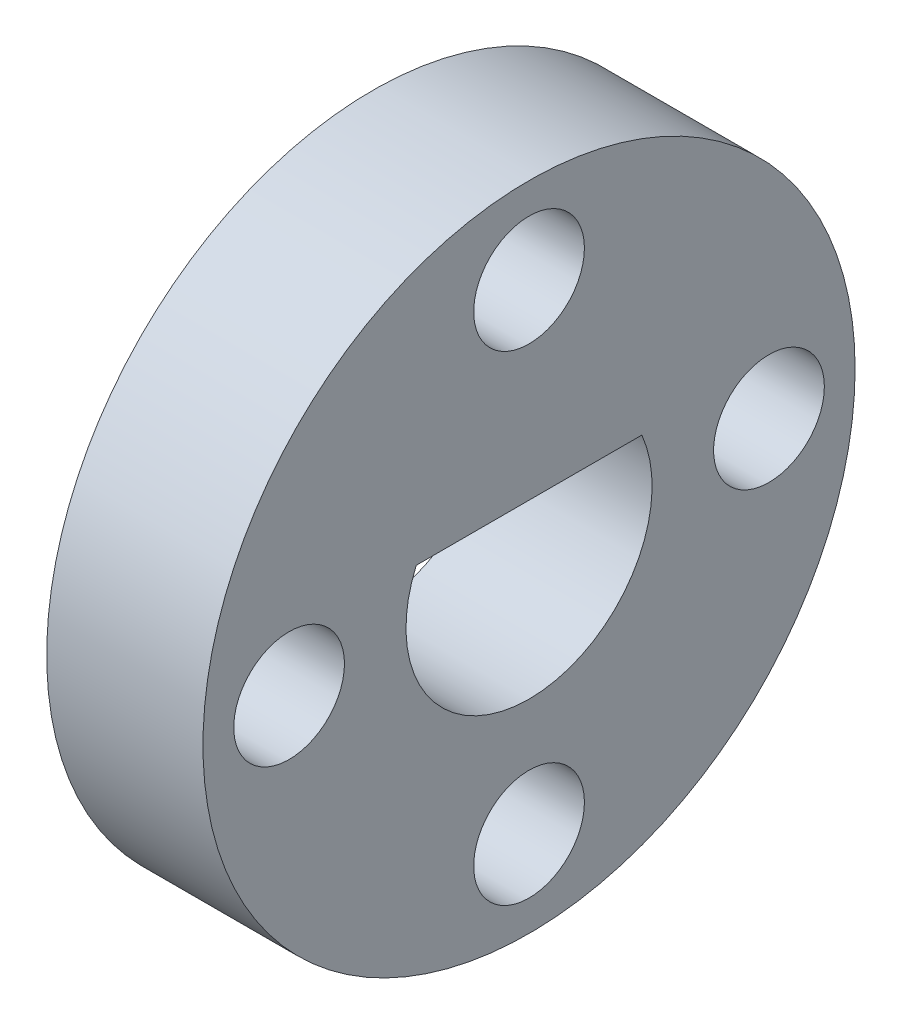
SolidWorks part; units mm, degrees
ref_plane "Front Plane" through (0, 0, 0) normal (0, 0, 1) x (1, 0, 0)
ref_plane "Top Plane" through (0, 0, 0) normal (0, 1, 0) x (1, 0, 0)
ref_plane "Right Plane" through (0, 0, 0) normal (1, 0, 0) x (0, 0, -1)
sketch "Sketch1" plane through (0, 0, 0) normal (1, 0, 0) x (0, 0, -1)
  line L0 (0, 0) -> (-13.25, 0) construction
  line L1 (-4.5826, 2) -> (4.5826, 2)
  line L2 (-8.3703, 5) -> (-12.2704, 5) construction
  circle A0 centre (0, 0) radius 13.25
  circle A1 centre (0, 0) radius 9.75 construction
  circle A2 centre (-9.75, 0) radius 2.25
  circle A3 centre (0, 9.75) radius 2.25
  circle A4 centre (9.75, 0) radius 2.25
  circle A5 centre (0, -9.75) radius 2.25
  arc A6 (-4.5826, 2) -> (4.5826, 2) centre (0, 0) ccw
  point P9 (0, 0)
  point P16 (0, 0)
  dimension "D1" = 19.5
  dimension "D2" = 4.5
  dimension "D3" = 26.5
  dimension "D5" = 10
  dimension "D6" = 3
  dimension "D4" = 4
extrude "Boss-Extrude1" add sketch "Sketch1" along normal blind 6.35
